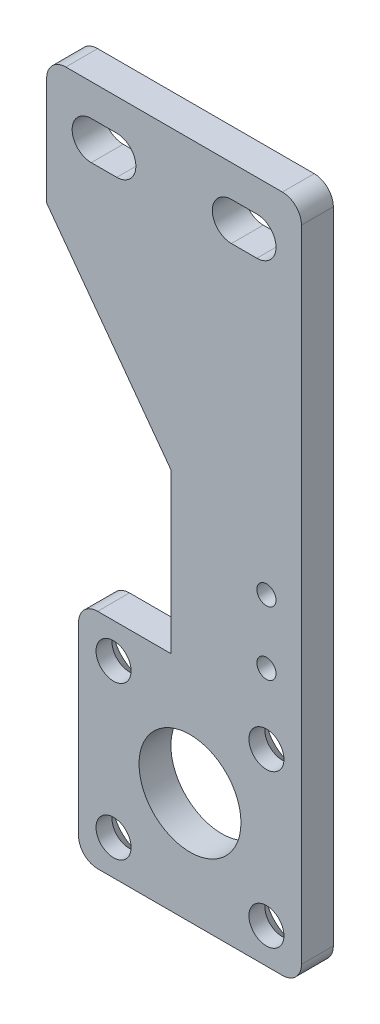
SolidWorks part; units mm, degrees
ref_plane "前视基准面" through (0, 0, 0) normal (0, 0, 1) x (1, 0, 0)
ref_plane "上视基准面" through (0, 0, 0) normal (0, 1, 0) x (1, 0, 0)
ref_plane "右视基准面" through (0, 0, 0) normal (1, 0, 0) x (0, 0, -1)
sketch "草图1" plane through (0, 0, 0) normal (0, 0, 1) x (1, 0, 0)
  line L48 (1708.4205, 1091.5655) -> (1727.9205, 1065.0655)
  line L49 (1727.9205, 1040.0655) -> (1727.9205, 1065.0655)
  line L50 (1713.4205, 1037.0655) -> (1713.4205, 1008.0655)
  line L51 (1716.4205, 1040.0655) -> (1727.9205, 1040.0655)
  line L52 (1719.4205, 1106.5655) -> (1715.4205, 1106.5655)
  line L53 (1715.4205, 1100.5655) -> (1719.4205, 1100.5655)
  line L54 (1737.4205, 1106.5655) -> (1741.4205, 1106.5655)
  line L55 (1741.4205, 1100.5655) -> (1737.4205, 1100.5655)
  line L56 (1748.4205, 1008.0655) -> (1748.4205, 1109.0655)
  line L57 (1708.4205, 1091.5655) -> (1708.4205, 1108.5655)
  line L58 (1716.4205, 1005.0655) -> (1745.4205, 1005.0655)
  line L59 (1711.4205, 1111.5655) -> (1745.4205, 1111.5655)
  line L84 (1736.5948, 1034.5655) -> (1749.7517, 1034.5655) construction
  line L85 (1742.9205, 1040.8701) -> (1742.9205, 1027.506) construction
  line L86 (1742.9205, 1016.8701) -> (1742.9205, 1003.506) construction
  line L87 (1736.5948, 1010.5655) -> (1749.7517, 1010.5655) construction
  line L88 (1718.9205, 1016.8701) -> (1718.9205, 1003.506) construction
  line L89 (1712.5948, 1010.5655) -> (1725.7517, 1010.5655) construction
  line L90 (1718.9205, 1040.8701) -> (1718.9205, 1027.506) construction
  line L91 (1712.5948, 1034.5655) -> (1725.7517, 1034.5655) construction
  line L92 (1715.2655, 1022.5655) -> (1745.6764, 1022.5655) construction
  line L93 (1730.9205, 1035.4766) -> (1730.9205, 1008.8792) construction
  line L94 (1740.1336, 1055.5655) -> (1746.3465, 1055.5655) construction
  line L95 (1742.9205, 1052.8568) -> (1742.9205, 1058.9795) construction
  line L96 (1742.9205, 1042.8568) -> (1742.9205, 1048.9795) construction
  line L97 (1740.1336, 1045.5655) -> (1746.3465, 1045.5655) construction
  line L98 (1732.3256, 1103.5655) -> (1745.7885, 1103.5655) construction
  line L99 (1741.4205, 1107.7087) -> (1741.4205, 1099.3923) construction
  line L100 (1737.4205, 1107.9379) -> (1737.4205, 1099.425) construction
  line L101 (1715.4205, 1107.9379) -> (1715.4205, 1099.425) construction
  line L102 (1719.4205, 1107.7087) -> (1719.4205, 1099.3923) construction
  line L103 (1710.3256, 1103.5655) -> (1723.7885, 1103.5655) construction
  circle A4 centre (1742.9205, 1045.5655) radius 1.5
  circle A7 centre (1742.9205, 1055.5655) radius 1.5
  circle A8 centre (1718.9205, 1034.5655) radius 2.75
  circle A9 centre (1718.9205, 1010.5655) radius 2.75
  circle A10 centre (1742.9205, 1010.5655) radius 2.75
  circle A11 centre (1742.9205, 1034.5655) radius 2.75
  circle A12 centre (1730.9205, 1022.5655) radius 8
  arc A13 (1737.4205, 1106.5655) -> (1737.4205, 1100.5655) centre (1737.4205, 1103.5655) ccw
  arc A14 (1715.4205, 1106.5655) -> (1715.4205, 1100.5655) centre (1715.4205, 1103.5655) ccw
  arc A15 (1719.4205, 1100.5655) -> (1719.4205, 1106.5655) centre (1719.4205, 1103.5655) ccw
  arc A16 (1741.4205, 1100.5655) -> (1741.4205, 1106.5655) centre (1741.4205, 1103.5655) ccw
  arc A17 (1711.4205, 1111.5655) -> (1708.4205, 1108.5655) centre (1711.4205, 1108.5655) ccw
  arc A18 (1748.4205, 1108.5655) -> (1745.4205, 1111.5655) centre (1745.4205, 1108.5655) ccw
  arc A19 (1713.4205, 1008.0655) -> (1716.4205, 1005.0655) centre (1716.4205, 1008.0655) ccw
  arc A20 (1745.4205, 1005.0655) -> (1748.4205, 1008.0655) centre (1745.4205, 1008.0655) ccw
  arc A21 (1716.4205, 1040.0655) -> (1713.4205, 1037.0655) centre (1716.4205, 1037.0655) ccw
extrude "拉伸1" add sketch "草图1" along normal blind 5 contours L51 A21 L50 A19 L58 A20 L56 A18 L59 A17 L57 L48 L49 A4 A7 A8 A9 A10 A11 A12 A15 L53 A14 L52 A16 L55 A13 L54
chamfer "倒角1" distance 2.5 angle 45 4 edges at (1745.6705, 1010.5655, 0) (1721.6705, 1010.5655, 0) (1721.6705, 1034.5655, 0) (1745.6705, 1034.5655, 0)
